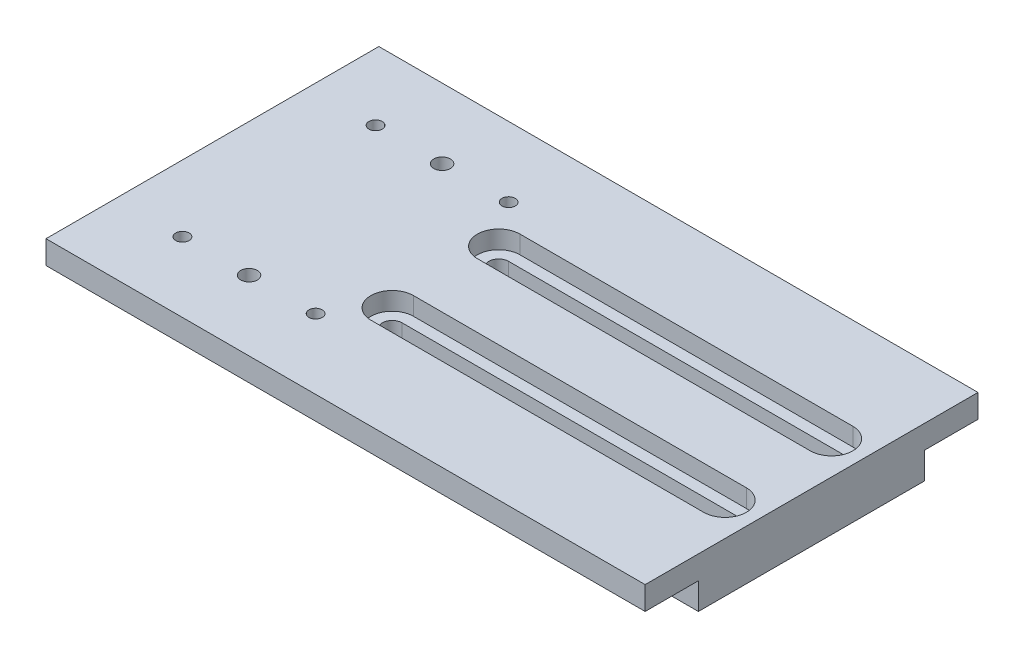
SolidWorks part; units mm, degrees
ref_plane "Ebene vorne" through (0, 0, 0) normal (0, 0, 1) x (1, 0, 0)
ref_plane "Ebene oben" through (0, 0, 0) normal (0, 1, 0) x (1, 0, 0)
ref_plane "Ebene rechts" through (0, 0, 0) normal (1, 0, 0) x (0, 0, -1)
sketch "Skizze1" plane through (0, 0, 0) normal (0, 1, 0) x (1, 0, 0)
  line L1 (-45, -25) -> (45, -25)
  line L2 (-45, -25) -> (-45, 25)
  line L3 (-45, 25) -> (45, 25)
  line L4 (45, -25) -> (45, 25)
  line L5 (-45, -25) -> (45, 25) construction
  line L6 (-45, 25) -> (45, -25) construction
  point P0 (0, 0)
  dimension "D1" = 90
  dimension "D2" = 50
extrude "Aufsatz-Linear austragen1" add sketch "Skizze1" along normal blind 7.5
sketch "Skizze2" plane through (0, 7.5, 0) normal (0, 1, 0) x (1, 0, 0)
  line L0 (0, 0) -> (-50.8024, 0) construction
  line L2 (-10, 8) -> (40, 8) construction
  line L3 (-10, 9.5) -> (40, 9.5)
  line L4 (-10, 6.5) -> (40, 6.5)
  line L5 (45, -25) -> (45, 25) construction
  line L6 (-10, -8) -> (40, -8) construction
  line L7 (-10, -9.5) -> (40, -9.5)
  line L8 (-10, -6.5) -> (40, -6.5)
  line L9 (-55, 0) -> (55, 0) construction
  line L12 (-45, 25) -> (-45, -25) construction
  line L13 (-65, 14.5) -> (-3.5026, 14.5) construction
  line L14 (-65, 14.5) -> (-35.1142, 17.1147) construction
  arc A20 (-10, 9.5) -> (-10, 6.5) centre (-10, 8) ccw
  arc A21 (40, 6.5) -> (40, 9.5) centre (40, 8) ccw
  arc A22 (-10, -9.5) -> (-10, -6.5) centre (-10, -8) cw
  arc A23 (40, -6.5) -> (40, -9.5) centre (40, -8) cw
  circle A52 centre (-35, 14.5) radius 1
  circle A54 centre (-15, 14.5) radius 1
  circle A91 centre (-35, -14.5) radius 1
  circle A93 centre (-15, -14.5) radius 1
  point P5 (-65, 14.5)
  point P36 (-55, 15)
  point P37 (-65, 15)
  point P39 (15, 8)
  point P48 (15, -8)
  dimension "D6" = 1.5
  dimension "D5" = 14.5
  dimension "D19" = 2
  dimension "D22" = 2
  dimension "D2" = 20
  dimension "D7" = 5
  dimension "D8" = 50
  dimension "D9" = 8
  dimension "D20" = 30
  dimension "D24" = 20
extrude "Schnitt-Linear austragen1" cut sketch "Skizze2" against normal through all
sketch "Skizze3" plane through (0, 7.5, 0) normal (0, 1, 0) x (1, 0, 0)
  line L0 (-10, 8) -> (40, 8) construction
  line L1 (-10, 11.2) -> (40, 11.2)
  line L2 (-10, 4.8) -> (40, 4.8)
  line L3 (-55, 0) -> (55, 0) construction
  line L4 (-10, -8) -> (40, -8) construction
  line L5 (-10, -11.2) -> (40, -11.2)
  line L6 (-10, -4.8) -> (40, -4.8)
  arc A0 (-10, 11.2) -> (-10, 4.8) centre (-10, 8) ccw
  arc A1 (40, 4.8) -> (40, 11.2) centre (40, 8) ccw
  arc A2 (-10, -11.2) -> (-10, -4.8) centre (-10, -8) cw
  arc A3 (40, -4.8) -> (40, -11.2) centre (40, -8) cw
  point P4 (15, 8)
  point P13 (15, -8)
  dimension "D1" = 3.2
extrude "Schnitt-Linear austragen2" cut sketch "Skizze3" against normal blind 2.7
sketch "Skizze6" plane through (-45, 0, 0) normal (-1, 0, 0) x (0, 0, 1)
  line L0 (27.5, 0) -> (-27.5, 0) construction
  line L1 (-17, 0) -> (-30, 0)
  line L2 (-17, 0) -> (-17, 4)
  line L3 (-17, 4) -> (-30, 4)
  line L4 (-30, 0) -> (-30, 4)
  line L6 (0, -4.125) -> (0, 4.125) construction
  line L7 (30, 0) -> (30, 4)
  line L8 (17, 4) -> (30, 4)
  line L9 (17, 0) -> (17, 4)
  line L10 (17, 0) -> (30, 0)
  dimension "D1" = 4
  dimension "D2" = 17
extrude "Schnitt-Linear austragen5" cut sketch "Skizze6" against normal through all
hole_wizard "M3 Gewindebohrung1" positions "Skizze8" profile "Skizze9" tap size "M3" standard "DIN" end condition through all
sketch "Skizze8" plane through (0, 7.5, 0) normal (0, 1, 0) x (1, 0, 0)
  line L0 (-45, 25) -> (-45, -25) construction
  line L1 (-4.125, 0) -> (4.125, 0) construction
  point P0 (-25, 14.5)
  point P2 (-25, -14.5)
  dimension "D1" = 20
  dimension "D2" = 14.5
  dimension "D3" = 14.5
  dimension "D4" = 20
sketch "Skizze9" plane through (-25, 7.5, -14.5) normal (1, 0, 0) x (0, 0, 1)
  line L0 (0, 0) -> (0, 7.5)
  line L1 (0, 7.5) -> (1.25, 7.5)
  line L2 (1.25, 7.5) -> (1.25, 0)
  line L5 (1.25, 0) -> (0, 0)
  line L11 (0, -6.35) -> (0, 107.95) construction
  dimension "Bohrerdurchmesser" = 2.5
  dimension "Bohrungstiefe" = 7.5
cosmetic thread "Bohrungsgewinde1" parameters "D2"=3
cosmetic thread "Bohrungsgewinde2" parameters "D2"=3
